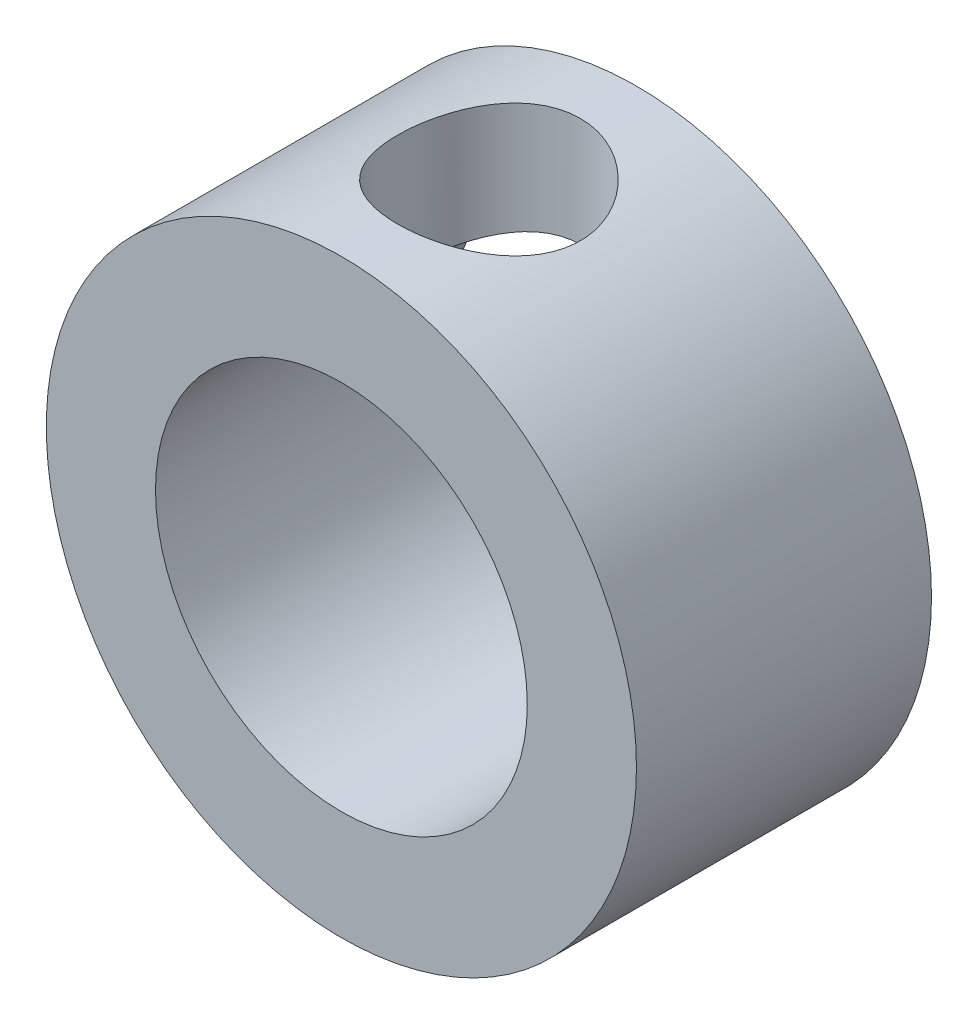
SolidWorks part; units mm, degrees
ref_plane "Front Plane" through (0, 0, 0) normal (0, 0, 1) x (1, 0, 0)
ref_plane "Top Plane" through (0, 0, 0) normal (0, 1, 0) x (1, 0, 0)
ref_plane "Right Plane" through (0, 0, 0) normal (1, 0, 0) x (0, 0, -1)
sketch "Sketch1" plane through (0, 0, 0) normal (0, 0, 1) x (1, 0, 0)
  circle A0 centre (0, 0) radius 8.001
  circle A1 centre (0, 0) radius 12.7
  dimension "D1" = 16.002
  dimension "D2" = 25.4
extrude "Boss-Extrude1" add sketch "Sketch1" along normal blind 12.7
ref_plane "Plane1" through (0, 12.7, 0) normal (0, 1, 0) x (1, 0, 0)
sketch "Sketch2" plane through (0, 12.7, 0) normal (0, 1, 0) x (1, 0, 0)
  line L0 (0, 0) -> (0, -12.7) construction
  line L1 (-12.7, -12.7) -> (12.7, -12.7) construction
  circle A0 centre (0, -6.35) radius 3.937
  dimension "D1" = 7.874
extrude "Cut-Extrude1" cut sketch "Sketch2" against normal up to next
